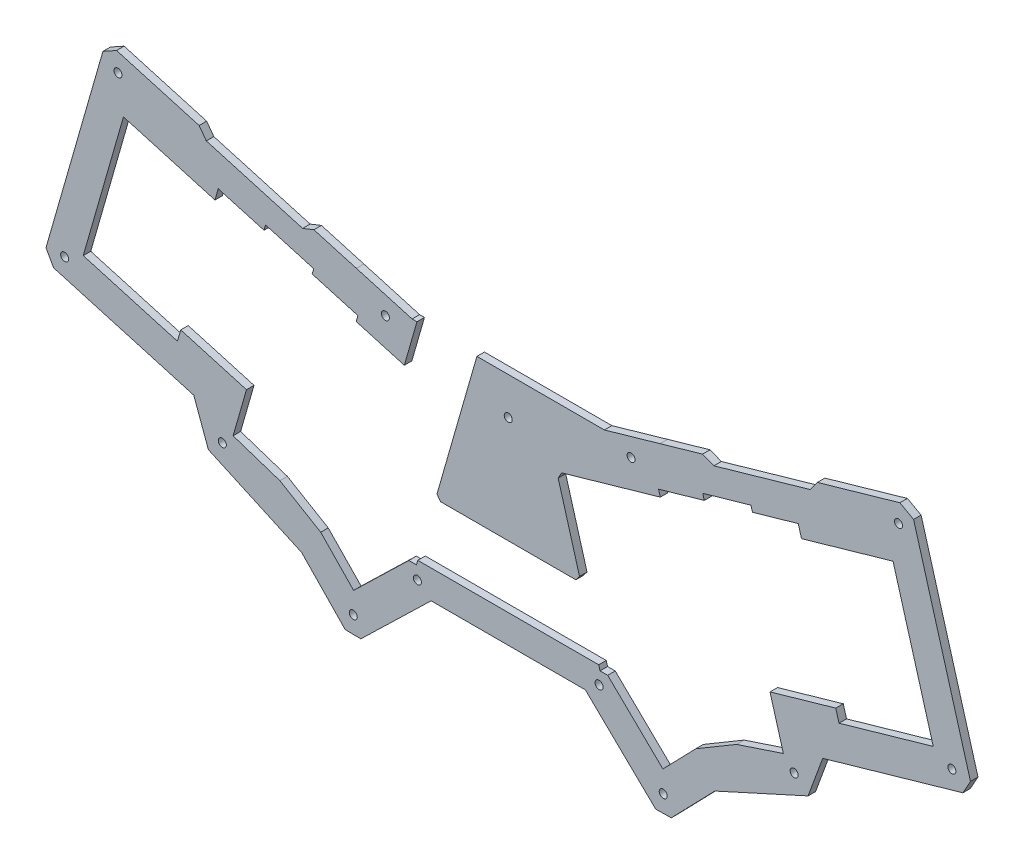
SolidWorks part; units mm, degrees
ref_plane "Plan de face" through (0, 0, 0) normal (0, 0, 1) x (1, 0, 0)
ref_plane "Plan de dessus" through (0, 0, 0) normal (0, 1, 0) x (1, 0, 0)
ref_plane "Plan de droite" through (0, 0, 0) normal (1, 0, 0) x (0, 0, -1)
sketch "Esquisse1" plane through (0, 0, 0) normal (0, 0, 1) x (1, 0, 0)
  line L0 (-121.6461, -32.0475) -> (-108.1875, -28.1884) construction
  line L1 (-108.1875, -28.1884) -> (-104.3283, -41.647) construction
  line L2 (-104.3283, -41.647) -> (-117.7869, -45.5062) construction
  line L3 (-117.7869, -45.5062) -> (-121.6461, -32.0475) construction
  line L4 (-100.1763, -37.9855) -> (-104.0355, -24.5269) construction
  line L5 (-104.0355, -24.5269) -> (-90.5769, -20.6677) construction
  line L6 (-90.5769, -20.6677) -> (-86.7177, -34.1263) construction
  line L7 (-86.7177, -34.1263) -> (-100.1763, -37.9855) construction
  line L8 (-82.5657, -30.4649) -> (-86.4249, -17.0063) construction
  line L9 (-86.4249, -17.0063) -> (-72.9663, -13.1471) construction
  line L10 (-72.9663, -13.1471) -> (-69.1071, -26.6057) construction
  line L11 (-69.1071, -26.6057) -> (-82.5657, -30.4649) construction
  line L12 (-63.6458, -27.5106) -> (-67.505, -14.0519) construction
  line L13 (-67.505, -14.0519) -> (-54.0463, -10.1927) construction
  line L14 (-54.0463, -10.1927) -> (-50.1872, -23.6514) construction
  line L15 (-50.1872, -23.6514) -> (-63.6458, -27.5106) construction
  line L16 (-44.0711, -26.8394) -> (-47.9303, -13.3808) construction
  line L17 (-47.9303, -13.3808) -> (-34.4717, -9.5216) construction
  line L18 (-34.4717, -9.5216) -> (-30.6125, -22.9802) construction
  line L19 (-30.6125, -22.9802) -> (-44.0711, -26.8394) construction
  line L20 (-25.8054, -21.6018) -> (-29.6646, -8.1432) construction
  line L21 (-29.6646, -8.1432) -> (-16.206, -4.284) construction
  line L22 (-16.206, -4.284) -> (-12.3468, -17.7426) construction
  line L23 (-12.3468, -17.7426) -> (-25.8054, -21.6018) construction
  line L24 (-116.4086, -50.3128) -> (-102.95, -46.4536) construction
  line L25 (-102.95, -46.4536) -> (-99.0908, -59.9122) construction
  line L26 (-99.0908, -59.9122) -> (-112.5494, -63.7714) construction
  line L27 (-112.5494, -63.7714) -> (-116.4086, -50.3128) construction
  line L28 (-98.798, -42.7922) -> (-85.3394, -38.933) construction
  line L29 (-85.3394, -38.933) -> (-81.4802, -52.3916) construction
  line L30 (-81.4802, -52.3916) -> (-94.9388, -56.2508) construction
  line L31 (-94.9388, -56.2508) -> (-98.798, -42.7922) construction
  line L32 (-81.1874, -35.2715) -> (-67.7288, -31.4123) construction
  line L33 (-67.7288, -31.4123) -> (-63.8696, -44.8709) construction
  line L34 (-63.8696, -44.8709) -> (-77.3282, -48.7301) construction
  line L35 (-77.3282, -48.7301) -> (-81.1874, -35.2715) construction
  line L36 (-62.2675, -32.3172) -> (-48.8089, -28.458) construction
  line L37 (-48.8089, -28.458) -> (-44.9497, -41.9166) construction
  line L38 (-44.9497, -41.9166) -> (-58.4083, -45.7758) construction
  line L39 (-58.4083, -45.7758) -> (-62.2675, -32.3172) construction
  line L40 (-42.6928, -31.646) -> (-29.2342, -27.7869) construction
  line L41 (-29.2342, -27.7869) -> (-25.375, -41.2455) construction
  line L42 (-25.375, -41.2455) -> (-38.8336, -45.1047) construction
  line L43 (-38.8336, -45.1047) -> (-42.6928, -31.646) construction
  line L44 (-24.4271, -26.4084) -> (-10.9685, -22.5492) construction
  line L45 (-10.9685, -22.5492) -> (-7.1093, -36.0078) construction
  line L46 (-7.1093, -36.0078) -> (-20.5679, -39.867) construction
  line L47 (-20.5679, -39.867) -> (-24.4271, -26.4084) construction
  line L48 (-19.1896, -44.6737) -> (-5.731, -40.8145) construction
  line L49 (-5.731, -40.8145) -> (-1.8718, -54.2731) construction
  line L50 (-1.8718, -54.2731) -> (-15.3304, -58.1323) construction
  line L51 (-15.3304, -58.1323) -> (-19.1896, -44.6737) construction
  line L52 (-37.4554, -49.9113) -> (-23.9967, -46.0521) construction
  line L53 (-23.9967, -46.0521) -> (-20.1376, -59.5107) construction
  line L54 (-20.1376, -59.5107) -> (-33.5962, -63.3699) construction
  line L55 (-33.5962, -63.3699) -> (-37.4554, -49.9113) construction
  line L56 (-57.03, -50.5825) -> (-43.5714, -46.7233) construction
  line L57 (-43.5714, -46.7233) -> (-39.7122, -60.1819) construction
  line L58 (-39.7122, -60.1819) -> (-53.1708, -64.0411) construction
  line L59 (-53.1708, -64.0411) -> (-57.03, -50.5825) construction
  line L60 (-75.9499, -53.5368) -> (-62.4913, -49.6776) construction
  line L61 (-62.4913, -49.6776) -> (-58.6321, -63.1362) construction
  line L62 (-58.6321, -63.1362) -> (-72.0908, -66.9954) construction
  line L63 (-72.0908, -66.9954) -> (-75.9499, -53.5368) construction
  line L64 (-93.5605, -61.0574) -> (-80.1019, -57.1982) construction
  line L65 (-80.1019, -57.1982) -> (-76.2427, -70.6569) construction
  line L66 (-76.2427, -70.6569) -> (-89.7013, -74.516) construction
  line L67 (-89.7013, -74.516) -> (-93.5605, -61.0574) construction
  line L68 (-111.1711, -68.5781) -> (-97.7125, -64.7189) construction
  line L69 (-97.7125, -64.7189) -> (-93.8533, -78.1775) construction
  line L70 (-93.8533, -78.1775) -> (-107.3119, -82.0367) construction
  line L71 (-107.3119, -82.0367) -> (-111.1711, -68.5781) construction
  line L72 (-79.0181, -77.3048) -> (-65.5595, -73.4456) construction
  line L73 (-65.5595, -73.4456) -> (-61.7003, -86.9042) construction
  line L74 (-61.7003, -86.9042) -> (-75.1589, -90.7634) construction
  line L75 (-75.1589, -90.7634) -> (-79.0181, -77.3048) construction
  line L76 (-99.4001, -88.1351) -> (-87.3916, -80.9362) construction
  line L77 (-87.3916, -80.9362) -> (-80.1927, -92.9448) construction
  line L78 (-80.1927, -92.9448) -> (-92.2012, -100.1436) construction
  line L79 (-92.2012, -100.1436) -> (-99.4001, -88.1351) construction
  line L80 (-120.0498, -100.4367) -> (-110.317, -90.3719) construction
  line L81 (-110.317, -90.3719) -> (-100.2522, -100.1047) construction
  line L82 (-100.2522, -100.1047) -> (-109.985, -110.1695) construction
  line L83 (-109.985, -110.1695) -> (-120.0498, -100.4367) construction
  line L86 (0.634, -55.7756) -> (-52.9527, -71.1413) construction
  line L89 (-59.2205, -88.2424) -> (-52.9527, -71.1413) construction
  line L96 (-93.4066, -103.0586) -> (-59.4637, -88.3612) construction
  line L97 (-105.418, -115.2057) -> (-93.9754, -103.3509) construction
  line L98 (-126.5332, -96.9919) -> (-107.5003, -115.385) construction
  line L99 (-167.7972, -50.1766) -> (-183.2082, -64.014) construction
  line L100 (-106.3822, -25.4572) -> (-123.6848, -30.4187) construction
  line L101 (-72.1178, -10.6906) -> (-88.4663, -15.3784) construction
  line L102 (-53.2337, -7.6163) -> (-70.5393, -12.5786) construction
  line L103 (-33.6604, -6.9452) -> (-50.9661, -11.9075) construction
  line L104 (-15.3965, -1.7081) -> (-31.745, -6.396) construction
  line L105 (0.5403, -55.2132) -> (-14.6896, -2.0999) construction
  line L106 (-16.199, -60.6113) -> (0.1495, -55.9235) construction
  line L107 (-52.7198, -71.0835) -> (-18.1144, -61.1606) construction
  line L108 (-59.1184, -88.0534) -> (-52.9674, -71.2752) construction
  line L109 (-183.2082, -64.014) -> (-173.1824, -64.9357) construction
  line L113 (-102.2678, -134.438) -> (-84.7238, -116.3191) construction
  line L114 (-84.7238, -116.3191) -> (-47.2969, -99.2981) construction
  line L115 (-47.2969, -99.2981) -> (-41.4917, -83.4594) construction
  line L116 (14.3812, -67.4381) -> (-41.4917, -83.4594) construction
  line L117 (17.8093, -61.2536) -> (-5.1371, 18.7701) construction
  line L122 (-11.3217, 22.1985) -> (-107.4545, -5.3614) construction
  line L129 (-167.7953, -27.6055) -> (-167.7953, -64.7189) construction
  line L130 (-242.0685, -103.8419) -> (-276.37, -88.2424) construction
  line L131 (-229.5108, -116.8112) -> (-242.0685, -103.8419) construction
  line L138 (-208.9328, -96.8551) -> (-229.5108, -116.8112) construction
  line L139 (-225.5107, -79.6567) -> (-208.9328, -96.8551) construction
  line L140 (-109.3352, -134.5492) -> (-102.2678, -134.438) construction
  line L142 (-5.1371, 18.7701) -> (-11.3217, 22.1985) construction
  line L143 (-211.4691, -30.6868) -> (-225.5107, -79.6567) construction
  line L147 (-114.18, -7.2899) -> (-107.4545, -5.3614) construction
  line L148 (-114.18, -7.2899) -> (-123.7936, -10.0465) construction
  line L154 (-118.7579, -16.9241) -> (-12.0005, 13.6817) construction
  line L155 (-131.531, -101.8802) -> (-105.9239, -126.7133) construction
  line L156 (-105.9239, -126.7133) -> (-89.4162, -109.6646) construction
  line L157 (-128.0942, -96.8551) -> (-106.0575, -118.2258)
  line L158 (-106.0575, -118.2258) -> (-92.9354, -104.6737)
  line L159 (-92.9354, -104.6737) -> (-58.4256, -88.9794) construction
  line L161 (1.8709, -56.4612) -> (-35.7408, -67.2462)
  line L162 (1.8709, -56.4612) -> (-14.1861, -0.4639)
  line L163 (-14.1861, -0.4639) -> (-50.7166, -10.9388)
  line L164 (-50.7166, -10.9388) -> (-52.026, -6.3725)
  line L165 (-52.026, -6.3725) -> (-70.2913, -11.61)
  line L166 (-70.2913, -11.61) -> (-70.911, -9.4488)
  line L167 (-70.911, -9.4488) -> (-90.1377, -14.9608)
  line L168 (-90.1377, -14.9608) -> (-89.5177, -17.1231)
  line L169 (-89.5177, -17.1231) -> (-107.783, -22.3606)
  line L170 (-107.783, -22.3606) -> (-107.0938, -24.7639)
  line L171 (-107.0938, -24.7639) -> (-146.5019, -36.064)
  line L174 (-89.4162, -109.6646) -> (-53.6562, -93.4017) construction
  line L175 (-53.6562, -93.4017) -> (-47.6042, -76.8897) construction
  line L176 (9.2923, -60.5749) -> (-47.6042, -76.8897) construction
  line L177 (9.2923, -60.5749) -> (-12.0005, 13.6817) construction
  line L178 (-229.7336, -25.4495) -> (-211.4691, -30.6868) construction
  line L179 (-229.0444, -23.0462) -> (-229.7336, -25.4495) construction
  line L180 (-173.1824, -64.9357) -> (-167.7972, -60.1004) construction
  line L181 (-247.3097, -17.8087) -> (-229.0444, -23.0462) construction
  line L185 (17.8093, -61.2536) -> (14.3812, -67.4381) construction
  line L186 (-183.2987, -65.7677) -> (-173.2729, -66.6895) construction
  line L187 (-173.2729, -66.6895) -> (-167.8052, -74.7882) construction
  line L190 (-246.6897, -15.6465) -> (-247.3097, -17.8087) construction
  line L191 (-263.9939, -10.6857) -> (-246.6897, -15.6465) construction
  line L192 (-264.6136, -12.8469) -> (-263.9939, -10.6857) construction
  line L193 (-282.8789, -7.6094) -> (-264.6136, -12.8469) construction
  line L194 (-284.1883, -12.1757) -> (-282.8789, -7.6094) construction
  line L195 (-320.7188, -1.7008) -> (-284.1883, -12.1757) construction
  line L196 (-336.2245, -55.7756) -> (-320.7188, -1.7008) construction
  line L197 (-183.2987, -65.7677) -> (-167.8052, -88.0782) construction
  line L198 (-181.8414, -71.5322) -> (-174.8684, -81.0171) construction
  line L199 (-174.8684, -81.0171) -> (-178.3549, -83.9622) construction
  line L200 (-344.8828, -60.5749) -> (-323.5901, 13.6817) construction
  line L201 (-344.8828, -60.5749) -> (-287.9863, -76.8897) construction
  line L202 (-281.9343, -93.4017) -> (-287.9863, -76.8897) construction
  line L203 (-246.1743, -109.6646) -> (-281.9343, -93.4017) construction
  line L206 (-228.4967, -24.7639) -> (-209.2751, -30.2756)
  line L207 (-227.8075, -22.3606) -> (-228.4967, -24.7639)
  line L208 (-246.0728, -17.1231) -> (-227.8075, -22.3606)
  line L209 (-245.4528, -14.9608) -> (-246.0728, -17.1231)
  line L210 (-264.6796, -9.4488) -> (-245.4528, -14.9608)
  line L211 (-265.2993, -11.61) -> (-264.6796, -9.4488)
  line L212 (-283.5645, -6.3725) -> (-265.2993, -11.61)
  line L213 (-284.8739, -10.9388) -> (-283.5645, -6.3725)
  line L217 (0.634, -55.7756) -> (-14.8717, -1.7008) construction
  line L220 (-14.8717, -1.7008) -> (-51.4022, -12.1757) construction
  line L221 (-51.4022, -12.1757) -> (-52.7116, -7.6094) construction
  line L222 (-52.7116, -7.6094) -> (-70.9769, -12.8469) construction
  line L223 (-70.9769, -12.8469) -> (-71.5966, -10.6857) construction
  line L224 (-71.5966, -10.6857) -> (-88.9008, -15.6465) construction
  line L225 (-88.9008, -15.6465) -> (-88.2808, -17.8087) construction
  line L226 (-88.2808, -17.8087) -> (-106.5461, -23.0462) construction
  line L227 (-106.5461, -23.0462) -> (-105.8569, -25.4495) construction
  line L228 (-105.8569, -25.4495) -> (-124.1214, -30.6868) construction
  line L231 (-124.1214, -30.6868) -> (-110.0799, -79.6567) construction
  line L232 (-110.0799, -79.6567) -> (-126.6577, -96.8551) construction
  line L233 (-126.6577, -96.8551) -> (-106.0797, -116.8112) construction
  line L234 (-106.0797, -116.8112) -> (-93.522, -103.8419) construction
  line L235 (-93.522, -103.8419) -> (-59.2205, -88.2424) construction
  line L236 (-321.4044, -0.4639) -> (-284.8739, -10.9388)
  line L237 (-337.4614, -56.4612) -> (-321.4044, -0.4639)
  line L238 (-337.4614, -56.4612) -> (-299.8497, -67.2462)
  line L241 (-229.5331, -118.2258) -> (-242.6551, -104.6737)
  line L242 (-208.2366, -97.573) -> (-229.5331, -118.2258)
  line L243 (-229.6666, -126.7133) -> (-246.1743, -109.6646) construction
  line L244 (-204.0596, -101.8802) -> (-229.6666, -126.7133) construction
  line L245 (-331.2803, 15.8863) -> (-193.4471, -23.6284) construction
  line L246 (-178.3549, -83.9622) -> (-185.8788, -75.0552) construction
  line L247 (-185.8788, -75.0552) -> (-181.8414, -71.5322) construction
  line L248 (-176.7625, -46.6332) -> (-185.5498, -54.5291) construction
  line L249 (-185.5498, -54.5291) -> (-181.1562, -59.4188) construction
  line L250 (-181.1562, -59.4188) -> (-172.3689, -51.5229) construction
  line L251 (-276.4721, -88.0534) -> (-282.6232, -71.2752) construction
  line L252 (-282.8707, -71.0835) -> (-317.4761, -61.1606) construction
  line L253 (-319.3915, -60.6113) -> (-335.74, -55.9235) construction
  line L254 (-336.1309, -55.2132) -> (-320.9009, -2.0999) construction
  line L255 (-320.194, -1.7081) -> (-303.8455, -6.396) construction
  line L256 (-301.9301, -6.9452) -> (-284.6245, -11.9075) construction
  line L257 (-282.3568, -7.6163) -> (-265.0512, -12.5786) construction
  line L258 (-263.4727, -10.6906) -> (-247.1242, -15.3784) construction
  line L259 (-229.2083, -25.4572) -> (-211.9057, -30.4187) construction
  line L260 (-172.3689, -51.5229) -> (-176.7625, -46.6332) construction
  line L261 (-209.0573, -96.9919) -> (-228.0902, -115.385) construction
  line L262 (-230.1725, -115.2057) -> (-241.6151, -103.3509) construction
  line L263 (-242.1839, -103.0586) -> (-276.1268, -88.3612) construction
  line L264 (-276.37, -88.2424) -> (-282.6379, -71.1413) construction
  line L265 (-336.2245, -55.7756) -> (-282.6379, -71.1413) construction
  line L268 (-353.3998, -61.2536) -> (-349.9717, -67.4381) construction
  line L274 (-221.4105, -7.2899) -> (-206.0252, -11.7015) construction
  line L275 (-221.4105, -7.2899) -> (-228.136, -5.3614) construction
  line L276 (-330.4534, 18.7701) -> (-324.2688, 22.1985) construction
  line L277 (-226.2553, -134.5492) -> (-233.3227, -134.438) construction
  line L281 (-324.2688, 22.1985) -> (-228.136, -5.3614) construction
  line L282 (-353.3998, -61.2536) -> (-330.4534, 18.7701) construction
  line L283 (-349.9717, -67.4381) -> (-294.0988, -83.4594) construction
  line L284 (-288.2936, -99.2981) -> (-294.0988, -83.4594) construction
  line L285 (-250.8667, -116.3191) -> (-288.2936, -99.2981) construction
  line L286 (-233.3227, -134.438) -> (-250.8667, -116.3191) construction
  line L288 (-225.6055, -110.1695) -> (-215.5407, -100.4367) construction
  line L289 (-235.3383, -100.1047) -> (-225.6055, -110.1695) construction
  line L290 (-225.2735, -90.3719) -> (-235.3383, -100.1047) construction
  line L291 (-215.5407, -100.4367) -> (-225.2735, -90.3719) construction
  line L292 (-243.3893, -100.1436) -> (-236.1904, -88.1351) construction
  line L293 (-255.3978, -92.9448) -> (-243.3893, -100.1436) construction
  line L294 (-248.1989, -80.9362) -> (-255.3978, -92.9448) construction
  line L295 (-236.1904, -88.1351) -> (-248.1989, -80.9362) construction
  line L296 (-260.4316, -90.7634) -> (-256.5724, -77.3048) construction
  line L297 (-273.8902, -86.9042) -> (-260.4316, -90.7634) construction
  line L298 (-270.031, -73.4456) -> (-273.8902, -86.9042) construction
  line L299 (-256.5724, -77.3048) -> (-270.031, -73.4456) construction
  line L300 (-228.2786, -82.0367) -> (-224.4194, -68.5781) construction
  line L301 (-241.7372, -78.1775) -> (-228.2786, -82.0367) construction
  line L302 (-237.878, -64.7189) -> (-241.7372, -78.1775) construction
  line L303 (-224.4194, -68.5781) -> (-237.878, -64.7189) construction
  line L304 (-245.8892, -74.516) -> (-242.03, -61.0574) construction
  line L305 (-259.3478, -70.6569) -> (-245.8892, -74.516) construction
  line L306 (-255.4886, -57.1982) -> (-259.3478, -70.6569) construction
  line L307 (-242.03, -61.0574) -> (-255.4886, -57.1982) construction
  line L308 (-263.4998, -66.9954) -> (-259.6406, -53.5368) construction
  line L309 (-276.9584, -63.1362) -> (-263.4998, -66.9954) construction
  line L310 (-273.0992, -49.6776) -> (-276.9584, -63.1362) construction
  line L311 (-259.6406, -53.5368) -> (-273.0992, -49.6776) construction
  line L312 (-282.4197, -64.0411) -> (-278.5605, -50.5825) construction
  line L313 (-295.8783, -60.1819) -> (-282.4197, -64.0411) construction
  line L314 (-292.0191, -46.7233) -> (-295.8783, -60.1819) construction
  line L315 (-278.5605, -50.5825) -> (-292.0191, -46.7233) construction
  line L316 (-301.9944, -63.3699) -> (-298.1352, -49.9113) construction
  line L317 (-315.453, -59.5107) -> (-301.9944, -63.3699) construction
  line L318 (-311.5938, -46.0521) -> (-315.453, -59.5107) construction
  line L319 (-298.1352, -49.9113) -> (-311.5938, -46.0521) construction
  line L320 (-320.2601, -58.1323) -> (-316.4009, -44.6737) construction
  line L321 (-333.7187, -54.2731) -> (-320.2601, -58.1323) construction
  line L322 (-329.8595, -40.8145) -> (-333.7187, -54.2731) construction
  line L323 (-316.4009, -44.6737) -> (-329.8595, -40.8145) construction
  line L324 (-315.0226, -39.867) -> (-311.1634, -26.4084) construction
  line L325 (-328.4812, -36.0078) -> (-315.0226, -39.867) construction
  line L326 (-324.622, -22.5492) -> (-328.4812, -36.0078) construction
  line L327 (-311.1634, -26.4084) -> (-324.622, -22.5492) construction
  line L328 (-296.7569, -45.1047) -> (-292.8977, -31.646) construction
  line L329 (-310.2155, -41.2455) -> (-296.7569, -45.1047) construction
  line L330 (-306.3563, -27.7869) -> (-310.2155, -41.2455) construction
  line L331 (-292.8977, -31.646) -> (-306.3563, -27.7869) construction
  line L332 (-277.1822, -45.7758) -> (-273.323, -32.3172) construction
  line L333 (-290.6408, -41.9166) -> (-277.1822, -45.7758) construction
  line L334 (-286.7817, -28.458) -> (-290.6408, -41.9166) construction
  line L335 (-273.323, -32.3172) -> (-286.7817, -28.458) construction
  line L336 (-258.2623, -48.7301) -> (-254.4031, -35.2715) construction
  line L337 (-271.7209, -44.8709) -> (-258.2623, -48.7301) construction
  line L338 (-267.8617, -31.4123) -> (-271.7209, -44.8709) construction
  line L339 (-254.4031, -35.2715) -> (-267.8617, -31.4123) construction
  line L340 (-240.6517, -56.2508) -> (-236.7925, -42.7922) construction
  line L341 (-254.1103, -52.3916) -> (-240.6517, -56.2508) construction
  line L342 (-250.2511, -38.933) -> (-254.1103, -52.3916) construction
  line L343 (-236.7925, -42.7922) -> (-250.2511, -38.933) construction
  line L344 (-223.0411, -63.7714) -> (-219.1819, -50.3128) construction
  line L345 (-236.4997, -59.9122) -> (-223.0411, -63.7714) construction
  line L346 (-232.6405, -46.4536) -> (-236.4997, -59.9122) construction
  line L347 (-219.1819, -50.3128) -> (-232.6405, -46.4536) construction
  line L348 (-323.2438, -17.7426) -> (-309.7851, -21.6018) construction
  line L349 (-319.3846, -4.284) -> (-323.2438, -17.7426) construction
  line L350 (-305.926, -8.1432) -> (-319.3846, -4.284) construction
  line L351 (-309.7851, -21.6018) -> (-305.926, -8.1432) construction
  line L352 (-304.978, -22.9802) -> (-291.5194, -26.8394) construction
  line L353 (-301.1188, -9.5216) -> (-304.978, -22.9802) construction
  line L354 (-287.6602, -13.3808) -> (-301.1188, -9.5216) construction
  line L355 (-291.5194, -26.8394) -> (-287.6602, -13.3808) construction
  line L356 (-285.4034, -23.6514) -> (-271.9448, -27.5106) construction
  line L357 (-281.5442, -10.1927) -> (-285.4034, -23.6514) construction
  line L358 (-268.0856, -14.0519) -> (-281.5442, -10.1927) construction
  line L359 (-271.9448, -27.5106) -> (-268.0856, -14.0519) construction
  line L360 (-266.4834, -26.6057) -> (-253.0248, -30.4649) construction
  line L361 (-262.6242, -13.1471) -> (-266.4834, -26.6057) construction
  line L362 (-249.1656, -17.0063) -> (-262.6242, -13.1471) construction
  line L363 (-253.0248, -30.4649) -> (-249.1656, -17.0063) construction
  line L364 (-248.8728, -34.1263) -> (-235.4142, -37.9855) construction
  line L365 (-245.0136, -20.6677) -> (-248.8728, -34.1263) construction
  line L366 (-231.555, -24.5269) -> (-245.0136, -20.6677) construction
  line L367 (-235.4142, -37.9855) -> (-231.555, -24.5269) construction
  line L368 (-217.8036, -45.5062) -> (-213.9444, -32.0475) construction
  line L369 (-231.2622, -41.647) -> (-217.8036, -45.5062) construction
  line L370 (-227.4031, -28.1884) -> (-231.2622, -41.647) construction
  line L371 (-213.9444, -32.0475) -> (-227.4031, -28.1884) construction
  line L372 (-226.2553, -134.5492) -> (-194.0347, -103.3509) construction
  line L373 (-109.3352, -134.5492) -> (-141.5559, -103.3509) construction
  line L374 (-141.5559, -103.3509) -> (-194.0347, -103.3509) construction
  line L375 (-167.7972, -50.1766) -> (-152.3861, -64.014) construction
  line L376 (-162.4119, -64.9357) -> (-167.7972, -60.1004) construction
  line L377 (-162.3376, -66.6895) -> (-167.8052, -74.7882) construction
  line L378 (-152.3118, -65.7677) -> (-167.8052, -88.0782) construction
  line L379 (-163.2254, -51.5229) -> (-158.8318, -46.6332) construction
  line L380 (-154.4381, -59.4188) -> (-163.2254, -51.5229) construction
  line L381 (-150.0445, -54.5291) -> (-154.4381, -59.4188) construction
  line L382 (-158.8318, -46.6332) -> (-150.0445, -54.5291) construction
  line L383 (-149.7316, -75.0552) -> (-153.7691, -71.5322) construction
  line L384 (-157.2555, -83.9622) -> (-149.7316, -75.0552) construction
  line L385 (-160.742, -81.0171) -> (-157.2555, -83.9622) construction
  line L386 (-153.7691, -71.5322) -> (-160.742, -81.0171) construction
  line L387 (-152.3118, -65.7677) -> (-162.3376, -66.6895) construction
  line L388 (-152.3861, -64.014) -> (-162.4119, -64.9357) construction
  line L389 (-206.0252, -11.7015) -> (-129.5654, -11.7015) construction
  line L393 (-146.9199, -47.4681) -> (-147.7987, -44.4031)
  line L394 (-167.1758, -11.7015) -> (-206.0252, -11.7015) construction
  line L395 (-154.4194, -21.3141) -> (-167.1758, -11.7015) construction
  line L396 (-123.7936, -10.0465) -> (-130.6498, -22.4155) construction
  line L399 (-129.5654, -11.7015) -> (-123.7936, -10.0465) construction
  line L400 (-129.4248, -12.7015) -> (-180.309, -12.7015)
  line L401 (-221.6861, -8.2511) -> (-206.1657, -12.7015)
  line L402 (-221.6861, -8.2511) -> (-228.4116, -6.3226)
  line L403 (-324.1462, 21.1231) -> (-291.1905, 11.6751)
  line L404 (-329.6063, 18.0963) -> (-324.1462, 21.1231)
  line L405 (-352.3244, -61.1311) -> (-329.6063, 18.0963)
  line L406 (-352.3244, -61.1311) -> (-349.2979, -66.591)
  line L407 (-349.2979, -66.591) -> (-293.3347, -82.6382)
  line L408 (-287.4987, -98.561) -> (-293.3347, -82.6382)
  line L409 (-250.2802, -115.4872) -> (-287.4987, -98.561)
  line L410 (-232.8926, -133.4446) -> (-250.2802, -115.4872)
  line L411 (-226.6535, -133.5428) -> (-232.8926, -133.4446)
  line L412 (-226.6535, -133.5428) -> (-198.5705, -106.3509)
  line L413 (-141.1511, -102.3509) -> (-194.4395, -102.3509) construction
  line L414 (-108.937, -133.5428) -> (-137.02, -106.3509)
  line L415 (-108.937, -133.5428) -> (-102.6979, -133.4446)
  line L416 (-102.6979, -133.4446) -> (-85.3104, -115.4872)
  line L417 (-85.3104, -115.4872) -> (-48.0918, -98.561)
  line L418 (-48.0918, -98.561) -> (-42.2558, -82.6382)
  line L419 (13.7074, -66.591) -> (-42.2558, -82.6382)
  line L420 (16.7339, -61.1311) -> (13.7074, -66.591)
  line L421 (16.7339, -61.1311) -> (-5.9842, 18.0963)
  line L422 (-5.9842, 18.0963) -> (-11.4443, 21.1231)
  line L423 (-11.4443, 21.1231) -> (-44.4001, 11.6751)
  line L424 (-113.9044, -8.2511) -> (-107.1789, -6.3226)
  line L425 (-113.9044, -8.2511) -> (-129.4248, -12.7015)
  line L426 (-167.1758, -12.7015) -> (-206.1657, -12.7015) construction
  line L427 (-113.9044, -8.2511) -> (-123.5179, -11.0078) construction
  line L430 (-208.2366, -97.573) -> (-207.4919, -96.8551)
  line L433 (-132.8889, -110.3509) -> (-202.7016, -110.3509) construction
  line L434 (-141.1511, -110.3509) -> (-194.4395, -110.3509) construction
  line L435 (-87.3916, -80.9362) -> (-92.2012, -100.1436) construction
  line L436 (-226.6535, -133.5428) -> (-194.4395, -102.3509) construction
  line L437 (-108.937, -133.5428) -> (-141.1511, -102.3509) construction
  line L438 (-65.5595, -73.4456) -> (-75.1589, -90.7634) construction
  line L439 (-59.5038, -49.2112) -> (-42.2001, -44.2495) construction
  line L440 (-92.8883, -102.8873) -> (-102.1438, -87.448) construction
  line L441 (-102.1438, -87.448) -> (-86.7045, -78.1925) construction
  line L442 (-86.7045, -78.1925) -> (-77.449, -93.6318) construction
  line L443 (-77.449, -93.6318) -> (-92.8883, -102.8873) construction
  line L444 (-76.5302, -93.2372) -> (-81.4919, -75.9335) construction
  line L445 (-81.4919, -75.9335) -> (-64.1883, -70.9718) construction
  line L446 (-64.1883, -70.9718) -> (-59.2265, -88.2755) construction
  line L447 (-59.2265, -88.2755) -> (-76.5302, -93.2372) construction
  line L448 (-42.2001, -44.2495) -> (-37.2384, -61.5531) construction
  line L449 (-37.2384, -61.5531) -> (-54.5421, -66.5149) construction
  line L450 (-54.5421, -66.5149) -> (-59.5038, -49.2112) construction
  line L451 (-76.6212, -95.0127) -> (-92.0605, -104.2682) construction
  line L452 (-92.9354, -104.6737) -> (-76.6212, -95.0127)
  line L453 (-76.6212, -95.0127) -> (-57.9612, -88.8254)
  line L454 (-39.9292, -48.5401) -> (-22.6255, -43.5783) construction
  line L455 (-22.6255, -43.5783) -> (-17.6638, -60.882) construction
  line L456 (-17.6638, -60.882) -> (-34.9674, -65.8437) construction
  line L457 (-34.9674, -65.8437) -> (-39.9292, -48.5401) construction
  line L458 (-63.102, -70.6603) -> (-58.1403, -87.964) construction
  line L459 (-36.9269, -62.6394) -> (-54.2306, -67.6011) construction
  line L460 (-36.0536, -66.1552) -> (-41.0154, -48.8515) construction
  line L461 (-57.9612, -88.8254) -> (-63.3014, -70.2021)
  line L462 (-37.0515, -62.6751) -> (-63.3014, -70.2021)
  line L463 (-37.0515, -62.6751) -> (-35.7408, -67.2462)
  line L464 (-298.539, -62.6751) -> (-299.8497, -67.2462)
  line L465 (-298.539, -62.6751) -> (-272.2891, -70.2021)
  line L466 (-277.6293, -88.8254) -> (-272.2891, -70.2021)
  line L467 (-258.9693, -95.0127) -> (-277.6293, -88.8254)
  line L468 (-242.6551, -104.6737) -> (-258.9693, -95.0127)
  line L469 (-98.0641, -3.7095) -> (-90.2165, -1.4597)
  line L470 (-94.657, -1.6925) -> (-56.2059, 9.3309) construction
  line L471 (-94.657, -1.6925) -> (-56.2059, 9.3309) construction
  line L474 (-98.0641, -3.7095) -> (-107.1789, -6.3226)
  line L476 (-11.4443, 21.1231) -> (-107.1789, -6.3226) construction
  line L481 (-237.5264, -3.7095) -> (-228.4116, -6.3226)
  line L482 (-66.4927, 2.2629) -> (-65.3792, -1.6212) construction
  line L483 (-324.1462, 21.1231) -> (-228.4116, -6.3226) construction
  line L484 (-85.7183, -3.2488) -> (-47.2672, 7.7746)
  line L485 (-90.2165, -1.4597) -> (-85.7183, -3.2488)
  line L486 (-44.4001, 11.6751) -> (-47.2672, 7.7746)
  line L487 (-291.1905, 11.6751) -> (-288.3233, 7.7746)
  line L488 (-249.8723, -3.2488) -> (-288.3233, 7.7746)
  line L489 (-245.374, -1.4597) -> (-249.8723, -3.2488)
  line L490 (-245.374, -1.4597) -> (-237.5264, -3.7095)
  line L491 (-134.9544, -108.3509) -> (-200.6361, -108.3509) construction
  line L492 (-137.02, -106.3509) -> (-198.5705, -106.3509)
  line L493 (-132.8889, -108.3509) -> (-202.7016, -108.3509) construction
  line L495 (-134.9544, -106.3509) -> (-200.6361, -106.3509) construction
  line L511 (-192.1766, -64.2267) -> (-167.7953, -64.7189) construction
  line L512 (-209.2751, -30.2756) -> (-204.2359, -12.7015)
  line L513 (-213.9586, -46.6087) -> (-210.0994, -33.1501) construction
  line L514 (-204.4396, -96.8551) -> (-203.9113, -95.0127)
  line L515 (-191.8496, -52.9484) -> (-182.1268, -19.0412) construction
  line L516 (-204.2359, -12.7015) -> (-206.1657, -12.7015)
  line L517 (-207.4919, -96.8551) -> (-204.4396, -96.8551)
  line L518 (-213.9586, -46.6087) -> (-204.2359, -12.7015) construction
  line L519 (-131.1509, -96.8551) -> (-131.6792, -95.0127)
  line L520 (-128.0942, -96.8551) -> (-131.1509, -96.8551)
  line L521 (-146.5019, -36.064) -> (-147.8731, -38.5378)
  line L522 (-203.9113, -95.0127) -> (-131.6792, -95.0127)
  line L523 (-140.7935, -70.2021) -> (-194.797, -70.2021)
  line L524 (-196.2457, -68.2796) -> (-180.309, -12.7015)
  line L525 (-139.3448, -68.2796) -> (-147.8731, -38.5378)
  line L526 (-139.3448, -68.2796) -> (-140.7935, -70.2021)
  line L527 (-194.797, -70.2021) -> (-196.2457, -68.2796)
  circle A2 centre (-12.0005, 13.6817) radius 1.6
  circle A3 centre (-12.0005, 13.6817) radius 3 construction
  circle A4 centre (-118.7579, -16.9241) radius 1.6
  circle A5 centre (9.2923, -60.5749) radius 1.6
  circle A6 centre (-53.6562, -93.4017) radius 1.6
  circle A7 centre (-105.9239, -126.7133) radius 1.6
  circle A8 centre (-131.531, -101.8802) radius 1.6
  circle A10 centre (-147.4897, -45.973) radius 1.6 construction
  circle A11 centre (-323.5901, 13.6817) radius 3 construction
  circle A12 centre (-188.1008, -45.973) radius 1.6 construction
  circle A14 centre (-204.0596, -101.8802) radius 1.6
  circle A15 centre (-229.6666, -126.7133) radius 1.6
  circle A16 centre (-281.9343, -93.4017) radius 1.6
  circle A17 centre (-344.8828, -60.5749) radius 1.6
  circle A18 centre (-216.8326, -16.9241) radius 1.6
  circle A19 centre (-323.5901, 13.6817) radius 1.6
  circle A20 centre (-167.7953, -27.6055) radius 1.6
  point P138 (-167.7953, -27.6055)
  point P139 (-6.5153, 23.5764)
  point P150 (-169.1046, -23.0392)
  point P172 (-65.3792, -1.6212)
  point P200 (19.1875, -66.0599)
  point P203 (-141.5228, -71.3355)
  point P204 (-141.5228, 1.5705)
  point P246 (-138.7935, -70.2021)
  point P263 (-133.4062, -12.8029)
  point P264 (-118.5195, -64.7189)
  point P283 (-140.1914, -70.9332)
  point P284 (-157.1758, -11.7015)
  point P308 (-196.797, -70.2021)
  point P405 (-354.778, -66.0599)
  point P406 (-329.0752, 23.5764)
  point P433 (-148.4244, -36.6152)
  point P470 (-75.4315, 3.8192)
  point P473 (-75.4315, 3.8192)
  dimension "D3" = 3.2
  dimension "D4" = 6
  dimension "D6" = 3.2
  dimension "D7" = 3.2
  dimension "D8" = 3.2
  dimension "D9" = 3.2
  dimension "D10" = 3.2
  dimension "D15" = 1.8424
  dimension "D16" = 3.2
  dimension "D5" = 1
  dimension "D14" = 2
  dimension "D21" = 1.61
  dimension "D22" = 2
  dimension "D23" = 1.1349
  dimension "D24" = 1.13
  dimension "D27" = 40
  dimension "D28" = 2
  dimension "D30" = 4
  dimension "D31" = 23
  dimension "D11" = 8
  dimension "D18" = 2
  dimension "D20" = 2
  dimension "D25" = 1.13
  dimension "D26" = 1.13
  dimension "D29" = 2
extrude "Boss.-Extru.1" add sketch "Esquisse1" along normal blind 3
sketch "Esquisse2" plane through (0, 0, 3) normal (0, 0, 1) x (1, 0, 0)
  line L0 (-167.7953, -110.3509) -> (-167.7953, -102.3509) construction
  line L1 (-132.8889, -110.3509) -> (-202.7016, -110.3509) construction
  line L2 (-168.7953, -110.3509) -> (-168.7953, -102.3509)
  line L3 (-166.7953, -110.3509) -> (-166.7953, -102.3509)
  line L4 (-163.7953, -110.3509) -> (-163.7953, -102.3509) construction
  line L5 (-164.7953, -110.3509) -> (-164.7953, -102.3509)
  line L6 (-162.7953, -110.3509) -> (-162.7953, -102.3509)
  line L7 (-159.7953, -110.3509) -> (-159.7953, -102.3509) construction
  line L8 (-160.7953, -110.3509) -> (-160.7953, -102.3509)
  line L9 (-158.7953, -110.3509) -> (-158.7953, -102.3509)
  line L10 (-155.7953, -110.3509) -> (-155.7953, -102.3509) construction
  line L11 (-156.7953, -110.3509) -> (-156.7953, -102.3509)
  line L12 (-154.7953, -110.3509) -> (-154.7953, -102.3509)
  line L13 (-151.7953, -110.3509) -> (-151.7953, -102.3509) construction
  line L14 (-152.7953, -110.3509) -> (-152.7953, -102.3509)
  line L15 (-150.7953, -110.3509) -> (-150.7953, -102.3509)
  line L16 (-147.7953, -110.3509) -> (-147.7953, -102.3509) construction
  line L17 (-148.7953, -110.3509) -> (-148.7953, -102.3509)
  line L18 (-146.7953, -110.3509) -> (-146.7953, -102.3509)
  line L19 (-171.7953, -110.3509) -> (-171.7953, -102.3509) construction
  line L20 (-172.7953, -110.3509) -> (-172.7953, -102.3509)
  line L21 (-170.7953, -110.3509) -> (-170.7953, -102.3509)
  line L22 (-175.7953, -110.3509) -> (-175.7953, -102.3509) construction
  line L23 (-176.7953, -110.3509) -> (-176.7953, -102.3509)
  line L24 (-174.7953, -110.3509) -> (-174.7953, -102.3509)
  line L25 (-179.7953, -110.3509) -> (-179.7953, -102.3509) construction
  line L26 (-180.7953, -110.3509) -> (-180.7953, -102.3509)
  line L27 (-178.7953, -110.3509) -> (-178.7953, -102.3509)
  line L28 (-183.7953, -110.3509) -> (-183.7953, -102.3509) construction
  line L29 (-184.7953, -110.3509) -> (-184.7953, -102.3509)
  line L30 (-182.7953, -110.3509) -> (-182.7953, -102.3509)
  line L31 (-187.7953, -110.3509) -> (-187.7953, -102.3509) construction
  line L32 (-188.7953, -110.3509) -> (-188.7953, -102.3509)
  line L33 (-186.7953, -110.3509) -> (-186.7953, -102.3509)
  arc A0 (-168.7953, -110.3509) -> (-166.7953, -110.3509) centre (-167.7953, -110.3509) ccw
  arc A1 (-166.7953, -102.3509) -> (-168.7953, -102.3509) centre (-167.7953, -102.3509) ccw
  arc A2 (-164.7953, -110.3509) -> (-162.7953, -110.3509) centre (-163.7953, -110.3509) ccw
  arc A3 (-162.7953, -102.3509) -> (-164.7953, -102.3509) centre (-163.7953, -102.3509) ccw
  arc A4 (-160.7953, -110.3509) -> (-158.7953, -110.3509) centre (-159.7953, -110.3509) ccw
  arc A5 (-158.7953, -102.3509) -> (-160.7953, -102.3509) centre (-159.7953, -102.3509) ccw
  arc A6 (-156.7953, -110.3509) -> (-154.7953, -110.3509) centre (-155.7953, -110.3509) ccw
  arc A7 (-154.7953, -102.3509) -> (-156.7953, -102.3509) centre (-155.7953, -102.3509) ccw
  arc A8 (-152.7953, -110.3509) -> (-150.7953, -110.3509) centre (-151.7953, -110.3509) ccw
  arc A9 (-150.7953, -102.3509) -> (-152.7953, -102.3509) centre (-151.7953, -102.3509) ccw
  arc A10 (-148.7953, -110.3509) -> (-146.7953, -110.3509) centre (-147.7953, -110.3509) ccw
  arc A11 (-146.7953, -102.3509) -> (-148.7953, -102.3509) centre (-147.7953, -102.3509) ccw
  arc A12 (-172.7953, -110.3509) -> (-170.7953, -110.3509) centre (-171.7953, -110.3509) ccw
  arc A13 (-170.7953, -102.3509) -> (-172.7953, -102.3509) centre (-171.7953, -102.3509) ccw
  arc A14 (-176.7953, -110.3509) -> (-174.7953, -110.3509) centre (-175.7953, -110.3509) ccw
  arc A15 (-174.7953, -102.3509) -> (-176.7953, -102.3509) centre (-175.7953, -102.3509) ccw
  arc A16 (-180.7953, -110.3509) -> (-178.7953, -110.3509) centre (-179.7953, -110.3509) ccw
  arc A17 (-178.7953, -102.3509) -> (-180.7953, -102.3509) centre (-179.7953, -102.3509) ccw
  arc A18 (-184.7953, -110.3509) -> (-182.7953, -110.3509) centre (-183.7953, -110.3509) ccw
  arc A19 (-182.7953, -102.3509) -> (-184.7953, -102.3509) centre (-183.7953, -102.3509) ccw
  arc A20 (-188.7953, -110.3509) -> (-186.7953, -110.3509) centre (-187.7953, -110.3509) ccw
  arc A21 (-186.7953, -102.3509) -> (-188.7953, -102.3509) centre (-187.7953, -102.3509) ccw
  point P4 (-167.7953, -106.3509)
  point P13 (-163.7953, -106.3509)
  point P20 (-159.7953, -106.3509)
  point P27 (-155.7953, -106.3509)
  point P34 (-151.7953, -106.3509)
  point P41 (-147.7953, -106.3509)
  point P47 (-171.7953, -106.3509)
  point P54 (-175.7953, -106.3509)
  point P61 (-179.7953, -106.3509)
  point P68 (-183.7953, -106.3509)
  point P75 (-187.7953, -106.3509)
  dimension "D1" = 6
  dimension "D2" = 6
